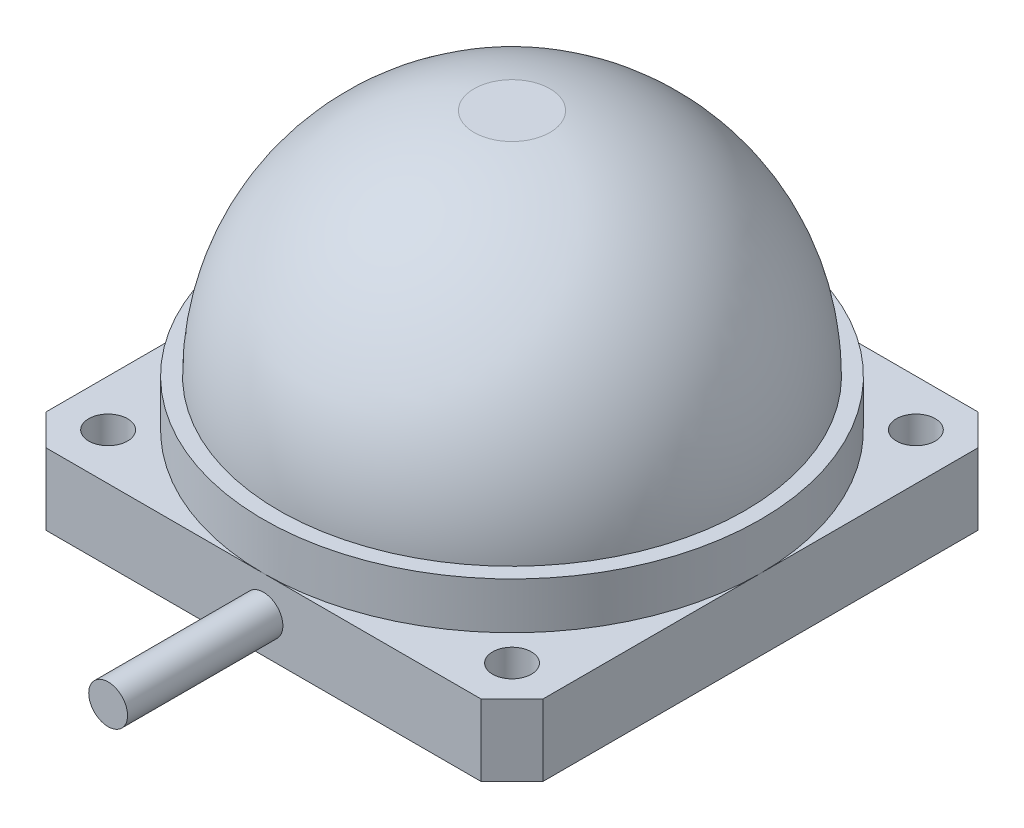
SolidWorks part; units mm, degrees
ref_plane "Front Plane" through (0, 0, 0) normal (0, 0, 1) x (1, 0, 0)
ref_plane "Top Plane" through (0, 0, 0) normal (0, 1, 0) x (1, 0, 0)
ref_plane "Right Plane" through (0, 0, 0) normal (1, 0, 0) x (0, 0, -1)
sketch "Sketch1" plane through (0, 0, 0) normal (0, 0, 1) x (1, 0, 0)
  line L0 (0, 15) -> (0, 0) construction
  line L1 (0, 0) -> (15, 0)
  line L2 (0, 15) -> (0, 0)
  arc A0 (15, 0) -> (0, 15) centre (0, 0) ccw
  dimension "D1" = 30
revolve "Revolve1" add sketch "Sketch1" angle 360 about L0
sketch "Sketch2" plane through (0, 0, 0) normal (0, -1, 0) x (1, 0, 0)
  circle A0 centre (0, 0) radius 16
  dimension "D1" = 32
extrude "Boss-Extrude1" add sketch "Sketch2" along normal blind 3
sketch "Sketch3" plane through (0, -3, 0) normal (0, -1, 0) x (1, 0, 0)
  line L1 (-16, -16) -> (16, -16)
  line L2 (-16, -16) -> (-16, 16)
  line L3 (-16, 16) -> (16, 16)
  line L4 (16, -16) -> (16, 16)
  line L5 (-16, -16) -> (16, 16) construction
  line L6 (-16, 16) -> (16, -16) construction
  circle A0 centre (0, 0) radius 16 construction
  point P0 (0, 0)
extrude "Boss-Extrude2" add sketch "Sketch3" along normal blind 4.6
hole_wizard "Ø2.5mm Dowel Hole1" positions "Sketch5" profile "Sketch7" hole size "Ø2.5" standard "ISO" end condition up to next
sketch "Sketch5" plane through (0, -3, 0) normal (0, 1, 0) x (1, 0, 0)
  line L1 (13, -13) -> (-13, -13)
  line L2 (13, -13) -> (13, 13)
  line L3 (13, 13) -> (-13, 13)
  line L4 (-13, -13) -> (-13, 13)
  line L5 (13, -13) -> (-13, 13) construction
  line L6 (13, 13) -> (-13, -13) construction
  point P0 (-13, 13)
  point P176 (13, -13)
  point P177 (13, 13)
  point P178 (-13, -13)
  point P190 (0, 0)
  dimension "D1" = 13
  dimension "D2" = 13
sketch "Sketch7" plane through (-13, -3, -13) normal (1, 0, 0) x (0, 0, 1)
  line L0 (0, 0) -> (0, 4.6)
  line L1 (0, 4.6) -> (1.25, 4.6)
  line L2 (1.25, 4.6) -> (1.25, 0)
  line L5 (1.25, 0) -> (0, 0)
  line L11 (0, -6.35) -> (0, 107.95) construction
  dimension "Thru Hole Dia." = 2.5
  dimension "Thru Hole Depth" = 4.6
chamfer "Chamfer1" distance 2 angle 45 3 edges at (16, -5.3, -16) (-16, -5.3, 16) (16, -5.3, 16)
sketch "Sketch11" plane through (0, 0, 16) normal (0, 0, 1) x (1, 0, 0)
  line L0 (14, -7.6) -> (-14, -7.6) construction
  circle A0 centre (0, -5.3) radius 1.25
  dimension "D1" = 2.5
  dimension "D2" = 2.3
extrude "Boss-Extrude3" add sketch "Sketch11" along normal blind 10
ref_plane "Plane1" through (0, 15, 0) normal (0, 1, 0) x (1, 0, 0)
ref_plane "Plane2" through (0, 14.8, 0) normal (0, 1, 0) x (1, 0, 0)
sketch "Sketch12" plane through (0, 14.8, 0) normal (0, 1, 0) x (1, 0, 0)
  circle A0 centre (0, 0) radius 16
  arc A1 (16, 0) -> (0, 16) centre (0, 0) ccw construction
extrude "Cut-Extrude1" cut sketch "Sketch12" along normal through all
